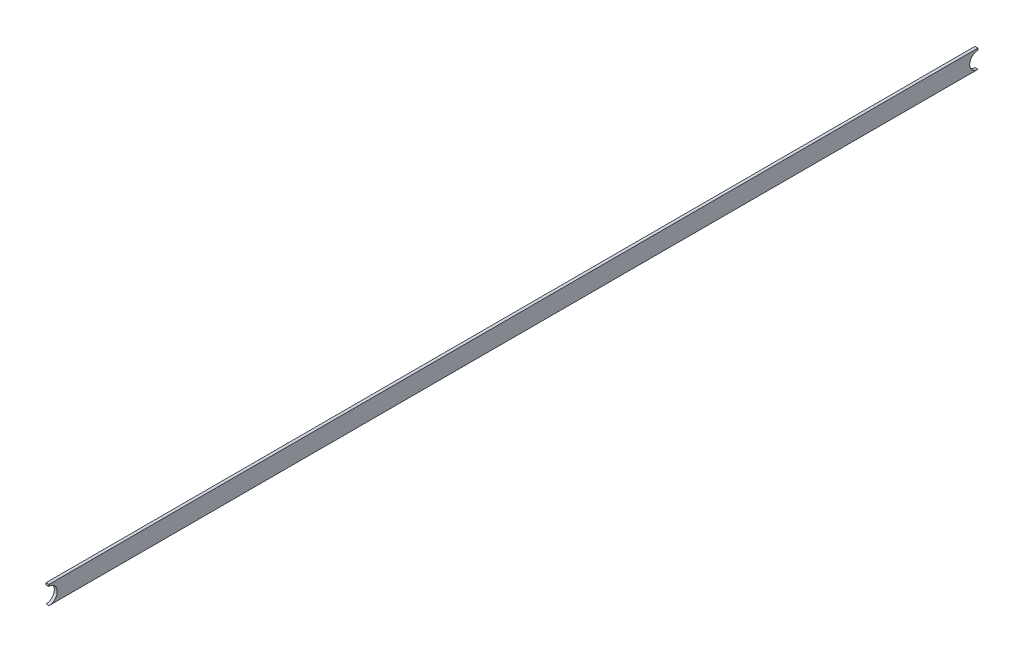
SolidWorks part; units mm, degrees
material "12Х18Н10Т ГОСТ 4543-71"
ref_plane "Спереди" through (0, 0, 0) normal (0, 0, 1) x (1, 0, 0)
ref_plane "Сверху" through (0, 0, 0) normal (0, 1, 0) x (1, 0, 0)
ref_plane "Справа" through (0, 0, 0) normal (1, 0, 0) x (0, 0, -1)
sketch "Эскиз1" plane through (0, 0, 0) normal (0, 0, 1) x (1, 0, 0)
  line L1 (-4, 25) -> (4, 25)
  line L2 (-4, 25) -> (-4, -25)
  line L3 (-4, -25) -> (4, -25)
  line L4 (4, 25) -> (4, -25)
  line L5 (0, -25) -> (0, 25) construction
  line L6 (-4, 0) -> (4, 0) construction
  point P64 (0, 0)
  dimension "D1" = 8
  dimension "D2" = 50
extrude "Бобышка-Вытянуть1" add sketch "Эскиз1" along normal mid plane 2475
sketch "Эскиз2" plane through (4, 0, 0) normal (1, 0, 0) x (0, 0, -1)
  line L0 (-1237.5, -25) -> (1237.5, -25) construction
  line L1 (-1237.5, -25) -> (-1237.5, 25) construction
  line L2 (-1237.5, 25) -> (-1260, 25)
  line L3 (-1237.5, -25) -> (-1260, -25)
  line L4 (-1260, 25) -> (-1260, 20)
  line L5 (-1237.5, -25) -> (-1237.5, 25)
  arc A0 (-1260, -25) -> (-1260, 20) centre (-1260, -2.5) ccw
  line M3 (-1237.5, 25) -> (-1237.5, -25)
  dimension "D1" = 45
extrude "Бобышка-Вытянуть2" add sketch "Эскиз2" against normal up to surface (8 mm away) contours A0 L2 L4 M3 | A0 L3 L5 up to face at (-4, 0, 0)
mirror "Зеркальное отражение1" about plane through (0, 0, 0) normal (0, 0, 1) of "Бобышка-Вытянуть2"
equation "\"расстояние между опорами фермы\"= 49"
equation "\"центр боковых направляющих\"= 1210 / 2"
equation "\"толщина полосы\"= 8"
equation "\"ширина полосы\"= 50"
equation "\"ширина боковой направляющей\"= 100 / 2"
equation "\"расстояние между центрами фиксатора\"= 178 / 2"
equation "\"D1@Эскиз1\"=\"толщина полосы\""
equation "\"D2@Эскиз1\"=\"ширина полосы\""
